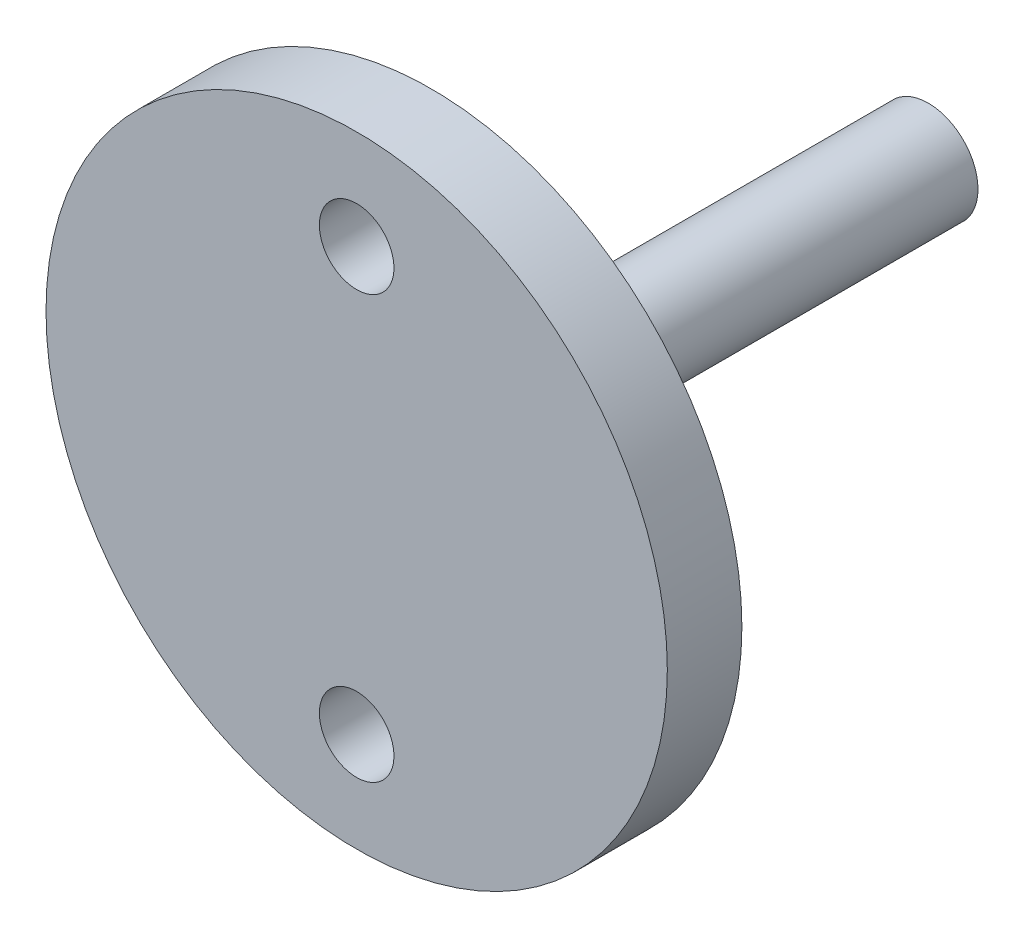
SolidWorks part; units mm, degrees
ref_plane "前视基准面" through (0, 0, 0) normal (0, 0, 1) x (1, 0, 0)
ref_plane "上视基准面" through (0, 0, 0) normal (0, 1, 0) x (1, 0, 0)
ref_plane "右视基准面" through (0, 0, 0) normal (1, 0, 0) x (0, 0, -1)
other "Configuration Table"
sketch "草图1" plane through (0, 0, 0) normal (0, 0, 1) x (1, 0, 0)
  circle A0 centre (0, 0) radius 12.5
  dimension "D1" = 25
extrude "凸台-拉伸1" add sketch "草图1" along normal blind 3
sketch "草图2" plane through (0, 0, 0) normal (0, 0, -1) x (-1, 0, 0)
  circle A0 centre (0, 0) radius 8.5 construction
  circle A1 centre (0, 8.5) radius 1.5
  circle A2 centre (0, -8.5) radius 1.5
  dimension "D1" = 17
  dimension "D2" = 3
  dimension "D3" = 3
extrude "切除-拉伸1" cut sketch "草图2" against normal blind 3
sketch "草图3" plane through (0, 0, 0) normal (0, 0, -1) x (-1, 0, 0)
  circle A0 centre (0, 0) radius 2
  dimension "D1" = 4
extrude "凸台-拉伸2" add sketch "草图3" along normal blind 20
